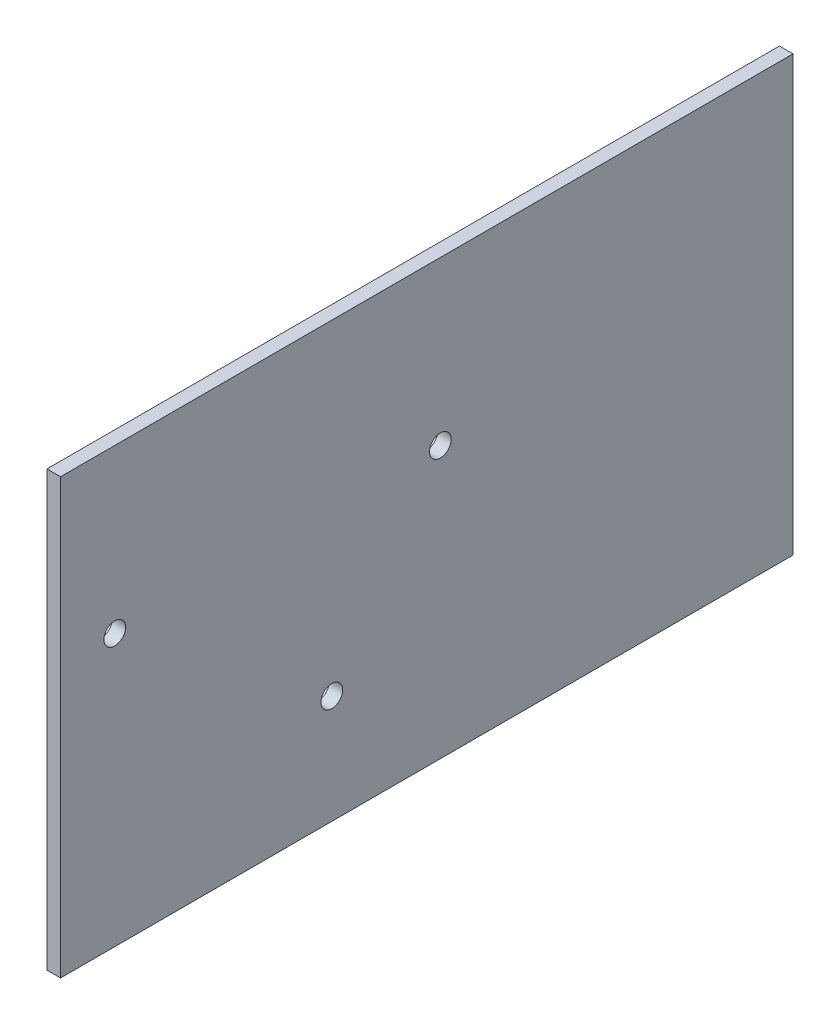
SolidWorks part; units mm, degrees
ref_plane "Front Plane" through (0, 0, 0) normal (0, 0, 1) x (1, 0, 0)
ref_plane "Top Plane" through (0, 0, 0) normal (0, 1, 0) x (1, 0, 0)
ref_plane "Right Plane" through (0, 0, 0) normal (1, 0, 0) x (0, 0, -1)
sketch "Sketch1" plane through (0, 0, 0) normal (1, 0, 0) x (0, 0, -1)
  line L1 (-70.2838, 99.91) -> (101.1662, 99.91)
  line L2 (-70.2838, 99.91) -> (-70.2838, -1.69)
  line L3 (-70.2838, -1.69) -> (101.1662, -1.69)
  line L4 (101.1662, 99.91) -> (101.1662, -1.69)
  circle A0 centre (-57.5838, 61.81) radius 2.54
  circle A1 centre (18.6162, 61.81) radius 2.54
  circle A2 centre (-6.7838, 23.71) radius 2.54
  dimension "D3" = 5.08
  dimension "D4" = 5.08
  dimension "D5" = 5.08
  dimension "D10" = 25.4
  dimension "D1" = 171.45
  dimension "D2" = 101.6
  dimension "D6" = 63.5
  dimension "D7" = 12.7
  dimension "D8" = 76.2
  dimension "D9" = 38.1
extrude "Boss-Extrude1" add sketch "Sketch1" against normal blind 3.175
